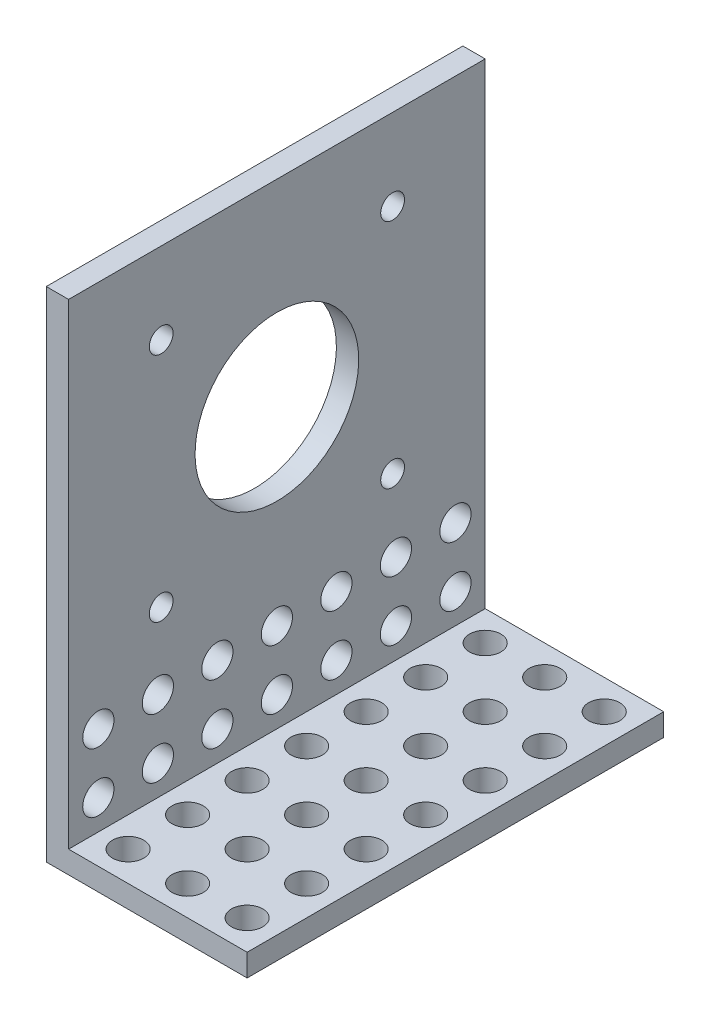
SolidWorks part; units mm, degrees
material "Alliage 6061"
ref_plane "Face" through (0, 0, 0) normal (0, 0, 1) x (1, 0, 0)
ref_plane "Dessus" through (0, 0, 0) normal (0, 1, 0) x (1, 0, 0)
ref_plane "Droite" through (0, 0, 0) normal (1, 0, 0) x (0, 0, -1)
sketch "Esquisse1" plane through (0, 0, 0) normal (0, 0, 1) x (1, 0, 0)
  line L0 (0, 64) -> (0, 0)
  line L1 (0, 0) -> (24, 0)
  dimension "D1" = 24
  dimension "D2" = 64
extrude "Extru.-Mince1" add sketch "Esquisse1" along normal mid plane 56 thin
sketch "Esquisse2" plane through (0, 0, 0) normal (0, 1, 0) x (1, 0, 0)
  line L0 (0, -28) -> (24, -28) construction
  line L1 (0, -28) -> (0, 28) construction
  circle A0 centre (4, -24) radius 2.1
  dimension "D1" = 4.2
  dimension "D2" = 4
  dimension "D3" = 4
extrude "Enlèv. mat.-Extru.1" cut sketch "Esquisse2" against normal through all
pattern_linear "Répétition linéaire1" count 3 spacing 8 along (1, 0, 0) count 7 spacing 8 along (0, 0, -1) of "Enlèv. mat.-Extru.1"
sketch "Esquisse3" plane through (0, 0, 0) normal (1, 0, 0) x (0, 0, -1)
  line L0 (-28, 0) -> (28, 0) construction
  line L1 (-28, 64) -> (-28, 0) construction
  circle A0 centre (-24, 4) radius 2.1
  dimension "D1" = 4.2
  dimension "D2" = 4
  dimension "D3" = 4
extrude "Enlèv. mat.-Extru.2" cut sketch "Esquisse3" against normal through all
pattern_linear "Répétition linéaire2" count 2 spacing 8 along (0, 1, 0) count 7 spacing 8 along (0, 0, -1) of "Enlèv. mat.-Extru.2"
sketch "Esquisse4" plane through (0, 0, 0) normal (1, 0, 0) x (0, 0, -1)
  line L0 (0, 64) -> (0, 0) construction
  line L1 (-28, 64) -> (28, 64) construction
  line L2 (-28, 0) -> (28, 0) construction
  circle A0 centre (0, 37.5) radius 11
  dimension "D1" = 22
  dimension "D2" = 37.5
extrude "Enlèv. mat.-Extru.3" cut sketch "Esquisse4" against normal through all
sketch "Esquisse5" plane through (0, 0, 0) normal (1, 0, 0) x (0, 0, -1)
  line L0 (0, 37.5) -> (-17.0155, 54.5155) construction
  line L1 (0, 37.5) -> (0, 56.19) construction
  circle A0 centre (0, 37.5) radius 22 construction
  circle A1 centre (-15.5563, 53.0563) radius 1.6
  dimension "D2" = 44
  dimension "D3" = 3.2
  dimension "D1" = 45
extrude "Enlèv. mat.-Extru.4" cut sketch "Esquisse5" against normal through all
pattern_circular "Répétition circulaire1" count 4 over 360 about axis through (0, 37.5, 0) along (1, 0, 0) of "Enlèv. mat.-Extru.4"
